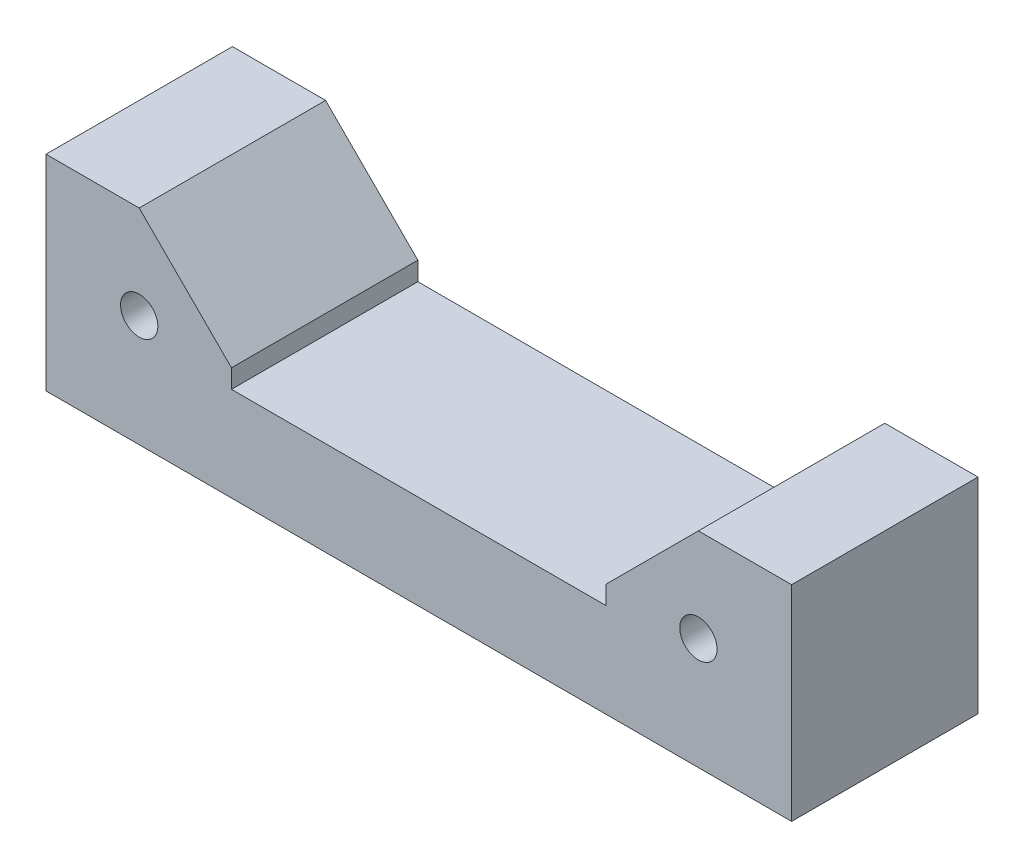
SolidWorks part; units mm, degrees
ref_plane "Front Plane" through (0, 0, 0) normal (0, 0, 1) x (1, 0, 0)
ref_plane "Top Plane" through (0, 0, 0) normal (0, 1, 0) x (1, 0, 0)
ref_plane "Right Plane" through (0, 0, 0) normal (1, 0, 0) x (0, 0, -1)
sketch "Sketch1" plane through (0, 0, 0) normal (0, 0, 1) x (1, 0, 0)
  line L0 (-20, 0) -> (20, 0)
  line L1 (-20, 0) -> (-20, 11)
  line L2 (-20, 11) -> (-15, 11)
  line L3 (-15, 11) -> (-10.0503, 6.0503)
  line L4 (-10.0503, 6.0503) -> (-10.0503, 5.0503)
  line L5 (-10.0503, 5.0503) -> (10.0503, 5.0503)
  line L6 (0, 12.7794) -> (0, -5.9809) construction
  line L7 (20, 0) -> (20, 11)
  line L8 (20, 11) -> (15, 11)
  line L9 (15, 11) -> (10.0503, 6.0503)
  line L10 (10.0503, 6.0503) -> (10.0503, 5.0503)
  circle A0 centre (-15, 6) radius 1
  circle A1 centre (15, 6) radius 1
  point P3 (0, 0)
  point P19 (0, 5.0503)
  dimension "D7" = 2
  dimension "D1" = 40
  dimension "D2" = 11
  dimension "D3" = 5
  dimension "D4" = 7
  dimension "D5" = 1
  dimension "D6" = 135
  dimension "D8" = 6
  dimension "D9" = 5
extrude "Boss-Extrude1" add sketch "Sketch1" along normal mid plane 10
